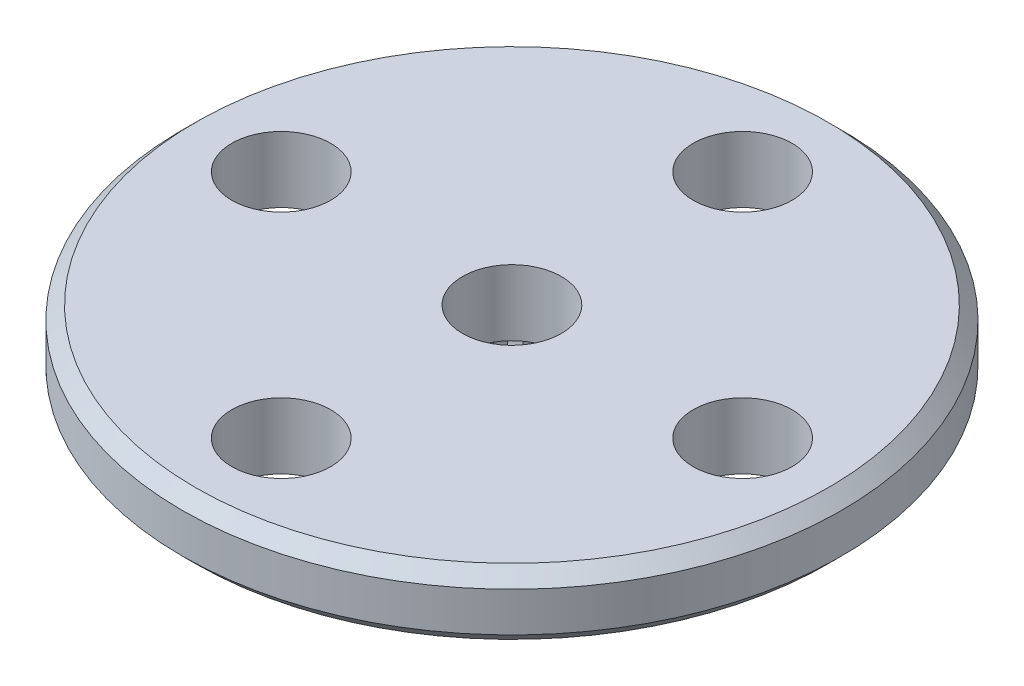
SolidWorks part; units mm, degrees
ref_plane "前视基准面" through (0, 0, 0) normal (0, 0, 1) x (1, 0, 0)
ref_plane "上视基准面" through (0, 0, 0) normal (0, 1, 0) x (1, 0, 0)
ref_plane "右视基准面" through (0, 0, 0) normal (1, 0, 0) x (0, 0, -1)
sketch "草图1" plane through (0, 0, 0) normal (0, 1, 0) x (1, 0, 0)
  line L0 (0, 0) -> (7, 0) construction
  line L1 (0, 0) -> (0, 7) construction
  line L2 (0, 0) -> (-7, 0) construction
  line L3 (0, 0) -> (0, -7) construction
  circle A0 centre (0, 0) radius 10
  circle A1 centre (0, 7) radius 1.5
  circle A2 centre (7, 0) radius 1.5
  circle A3 centre (-7, 0) radius 1.5
  circle A4 centre (0, -7) radius 1.5
  dimension "D1" = 20
  dimension "D3" = 3
  dimension "D4" = 3
  dimension "D5" = 3
  dimension "D6" = 3
  dimension "D2" = 7
extrude "凸台-拉伸2" add sketch "草图1" along normal blind 2
sketch "草图2" plane through (0, 0, 0) normal (0, 1, 0) x (1, 0, 0)
  line L0 (0, 0) -> (4.5, 0) construction
  line L1 (0, 0) -> (4.3586, 1.1191) construction
  line L2 (0, 0) -> (4.4645, 0.564) construction
  line L3 (2.5, 0) -> (2.9763, 0.376)
  line L4 (2.9763, 0.376) -> (2.4215, 0.6217)
  line L5 (2.4215, -0.6217) -> (2.9763, -0.376)
  line L6 (2.9763, -0.376) -> (2.5, 0)
  line L7 (2.1908, -1.2044) -> (2.7893, -1.1044)
  line L8 (2.7893, -1.1044) -> (2.4215, -0.6217)
  line L9 (1.8224, -1.7114) -> (2.4271, -1.7634)
  line L10 (2.4271, -1.7634) -> (2.1908, -1.2044)
  line L11 (1.3396, -2.1108) -> (1.9123, -2.3115)
  line L12 (1.9123, -2.3115) -> (1.8224, -1.7114)
  line L13 (0.7725, -2.3776) -> (1.2773, -2.7145)
  line L14 (1.2773, -2.7145) -> (1.3396, -2.1108)
  line L15 (0.157, -2.4951) -> (0.5621, -2.9469)
  line L16 (0.5621, -2.9469) -> (0.7725, -2.3776)
  line L17 (-0.4685, -2.4557) -> (-0.1884, -2.9941)
  line L18 (-0.1884, -2.9941) -> (0.157, -2.4951)
  line L19 (-1.0644, -2.2621) -> (-0.9271, -2.8532)
  line L20 (-0.9271, -2.8532) -> (-0.4685, -2.4557)
  line L21 (-1.5936, -1.9263) -> (-1.6075, -2.533)
  line L22 (-1.6075, -2.533) -> (-1.0644, -2.2621)
  line L23 (-2.0225, -1.4695) -> (-2.1869, -2.0536)
  line L24 (-2.1869, -2.0536) -> (-1.5936, -1.9263)
  line L25 (-2.3244, -0.9203) -> (-2.6289, -1.4453)
  line L26 (-2.6289, -1.4453) -> (-2.0225, -1.4695)
  line L27 (-2.4803, -0.3133) -> (-2.9057, -0.7461)
  line L28 (-2.9057, -0.7461) -> (-2.3244, -0.9203)
  line L29 (-2.4803, 0.3133) -> (-3, 0)
  line L30 (-3, 0) -> (-2.4803, -0.3133)
  line L31 (-2.3244, 0.9203) -> (-2.9057, 0.7461)
  line L32 (-2.9057, 0.7461) -> (-2.4803, 0.3133)
  line L33 (-2.0225, 1.4695) -> (-2.6289, 1.4453)
  line L34 (-2.6289, 1.4453) -> (-2.3244, 0.9203)
  line L35 (-1.5936, 1.9263) -> (-2.1869, 2.0536)
  line L36 (-2.1869, 2.0536) -> (-2.0225, 1.4695)
  line L37 (-1.0644, 2.2621) -> (-1.6075, 2.533)
  line L38 (-1.6075, 2.533) -> (-1.5936, 1.9263)
  line L39 (-0.4685, 2.4557) -> (-0.9271, 2.8532)
  line L40 (-0.9271, 2.8532) -> (-1.0644, 2.2621)
  line L41 (0.157, 2.4951) -> (-0.1884, 2.9941)
  line L42 (-0.1884, 2.9941) -> (-0.4685, 2.4557)
  line L43 (0.7725, 2.3776) -> (0.5621, 2.9469)
  line L44 (0.5621, 2.9469) -> (0.157, 2.4951)
  line L45 (1.3396, 2.1108) -> (1.2773, 2.7145)
  line L46 (1.2773, 2.7145) -> (0.7725, 2.3776)
  line L47 (1.8224, 1.7114) -> (1.9123, 2.3115)
  line L48 (1.9123, 2.3115) -> (1.3396, 2.1108)
  line L49 (2.1908, 1.2044) -> (2.4271, 1.7634)
  line L50 (2.4271, 1.7634) -> (1.8224, 1.7114)
  line L51 (2.4215, 0.6217) -> (2.7893, 1.1044)
  line L52 (2.7893, 1.1044) -> (2.1908, 1.2044)
  circle A0 centre (0, 0) radius 4.5
  circle A1 centre (0, 0) radius 3 construction
  circle A2 centre (0, 0) radius 2.5 construction
  point P86 (0, 0)
  dimension "D1" = 9
  dimension "D2" = 6
  dimension "D3" = 5
  dimension "D4" = 7.2
  dimension "D5" = 7.2
  dimension "D6" = 25
extrude "凸台-拉伸3" add sketch "草图2" against normal blind 2.9
sketch "草图4" plane through (0, 0, 0) normal (0, 0, 1) x (1, 0, 0)
  line L0 (0, -2.9) -> (0, -2.1289)
  line L1 (-4.5, -2.9) -> (4.5, -2.9) construction
  line L2 (0, -2.1289) -> (2.5, -2.1289)
  line L3 (2.5, -2.1289) -> (3.1367, -2.9)
  line L4 (3.1367, -2.9) -> (0, -2.9)
  dimension "D1" = 2.5
  dimension "D2" = 50.453
  dimension "D3" = 1
  dimension "D4" = 3.1367
revolve "切除-旋转1" cut sketch "草图4" angle 360 about L0
chamfer "倒角1" distance 0.4 angle 45 2 edges at (0, 0, 10) (0, 2, 10)
sketch "草图5" plane through (0, 0, 0) normal (0, 1, 0) x (1, 0, 0)
  circle A0 centre (0, 0) radius 1.5
  dimension "D1" = 3
extrude "切除-拉伸1" cut sketch "草图5" along normal blind 10
